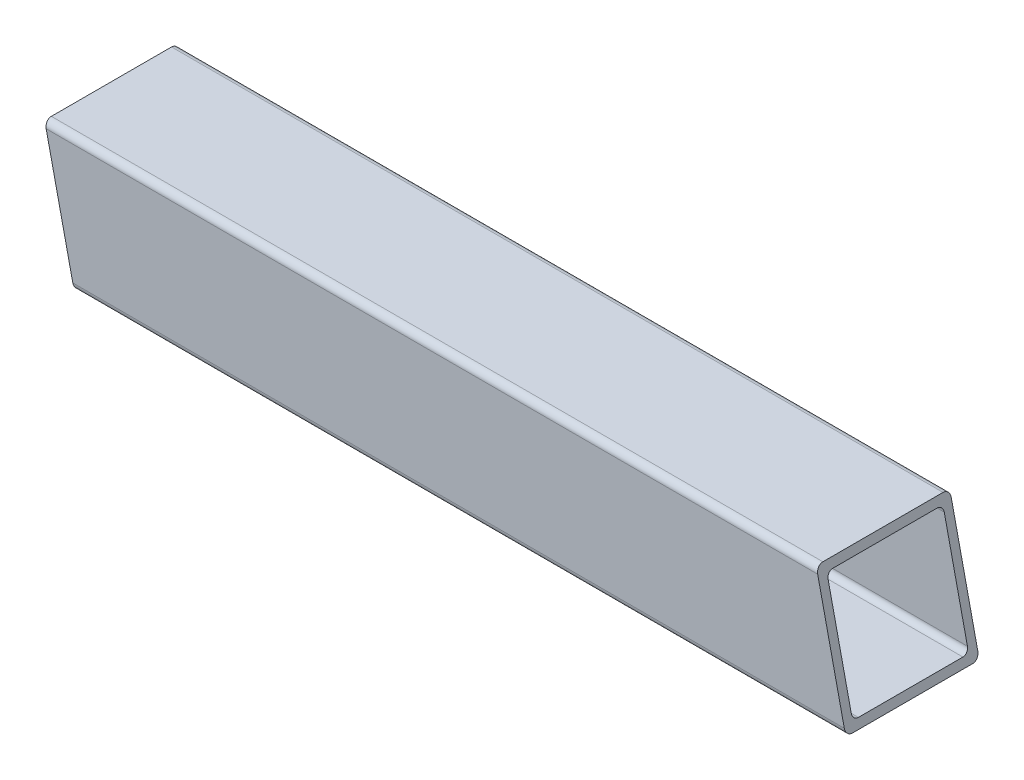
SolidWorks part; units mm, degrees
ref_plane "Front" through (0, 0, 0) normal (0, 0, 1) x (1, 0, 0)
ref_plane "Top" through (0, 0, 0) normal (0, 1, 0) x (1, 0, 0)
ref_plane "Right" through (0, 0, 0) normal (1, 0, 0) x (0, 0, -1)
sketch "Sketch1" plane through (0, 0, 0) normal (1, 0, 0) x (0, 0, -1)
  line L0 (-11.049, 0) -> (-12.7, 0) construction
  line L1 (11.43, -12.7) -> (-11.43, -12.7) construction
  line L2 (12.7, -11.43) -> (12.7, 11.43) construction
  line L3 (11.43, 12.7) -> (-11.43, 12.7) construction
  line L4 (-12.7, -11.43) -> (-12.7, 11.43) construction
  line L5 (12.7, -12.7) -> (-12.7, 12.7) construction
  line L6 (12.7, 12.7) -> (-12.7, -12.7) construction
  line L7 (9.9441, 11.049) -> (-9.9441, 11.049) construction
  line L8 (11.049, 9.9441) -> (11.049, -9.9441) construction
  line L9 (9.9441, -11.049) -> (-9.9441, -11.049) construction
  line L10 (-11.049, 9.9441) -> (-11.049, -9.9441) construction
  line L11 (11.049, 11.049) -> (-11.049, -11.049) construction
  line L12 (11.049, -11.049) -> (-11.049, 11.049) construction
  line L13 (0, -11.049) -> (0, -12.7) construction
  line L14 (11.049, -9.9441) -> (11.049, -12.7) construction
  line L15 (11.049, 0) -> (12.7, 0) construction
  line L16 (11.049, -12.7) -> (12.7, -12.7) construction
  arc A0 (-9.9441, -11.049) -> (-11.049, -9.9441) centre (-9.9441, -9.9441) cw construction
  arc A1 (11.049, -9.9441) -> (9.9441, -11.049) centre (9.9441, -9.9441) cw construction
  arc A2 (9.9441, 11.049) -> (11.049, 9.9441) centre (9.9441, 9.9441) cw construction
  arc A3 (-9.9441, 11.049) -> (-11.049, 9.9441) centre (-9.9441, 9.9441) ccw construction
  arc A4 (11.43, -12.7) -> (12.7, -11.43) centre (11.43, -11.43) ccw construction
  arc A5 (12.7, 11.43) -> (11.43, 12.7) centre (11.43, 11.43) ccw construction
  arc A6 (-11.43, 12.7) -> (-12.7, 11.43) centre (-11.43, 11.43) ccw construction
  arc A7 (-11.43, -12.7) -> (-12.7, -11.43) centre (-11.43, -11.43) cw construction
  point P0 (0, 0)
  point P6 (0, 0)
  dimension "D2" = 1.1049
  dimension "D3" = 1.27
  dimension "Outside Width" = 25.4
  dimension "Ouside Height" = 25.4
  dimension "Inside Height" = 22.098
  dimension "Wall Thickness" = 1.651
sketch "Sketch2" plane through (0, 0, 0) normal (0, 0, 1) x (1, 0, 0)
  line L0 (-76.2, 0) -> (76.2, 0) construction
  point P3 (-52.451, 0)
  point P4 (52.451, 0)
  dimension "Length" = 152.4
  dimension "D1" = 23.749
  dimension "D2" = 23.749
sketch "Sketch4" plane through (0, 0, 0) normal (1, 0, 0) x (0, 0, -1)
  line L8 (12.7, -11.43) -> (12.7, 11.43)
  line L9 (11.43, 12.7) -> (-11.43, 12.7)
  line L10 (-12.7, -11.43) -> (-12.7, 11.43)
  line L11 (11.43, -12.7) -> (-11.43, -12.7)
  line L12 (11.049, 9.9441) -> (11.049, -9.9441)
  line L13 (9.9441, -11.049) -> (-9.9441, -11.049)
  line L14 (-11.049, 9.9441) -> (-11.049, -9.9441)
  line L15 (9.9441, 11.049) -> (-9.9441, 11.049)
  arc A8 (12.7, 11.43) -> (11.43, 12.7) centre (11.43, 11.43) ccw
  arc A9 (-11.43, 12.7) -> (-12.7, 11.43) centre (-11.43, 11.43) ccw
  arc A10 (-12.7, -11.43) -> (-11.43, -12.7) centre (-11.43, -11.43) ccw
  arc A11 (11.43, -12.7) -> (12.7, -11.43) centre (11.43, -11.43) ccw
  arc A12 (9.9441, -11.049) -> (11.049, -9.9441) centre (9.9441, -9.9441) ccw
  arc A13 (-11.049, -9.9441) -> (-9.9441, -11.049) centre (-9.9441, -9.9441) ccw
  arc A14 (-9.9441, 11.049) -> (-11.049, 9.9441) centre (-9.9441, 9.9441) ccw
  arc A15 (11.049, 9.9441) -> (9.9441, 11.049) centre (9.9441, 9.9441) ccw
extrude "Boss-Extrude1" add sketch "Sketch4" along normal up to vertex (76.2 mm away) and the other way up to vertex (76.2 mm away)
sketch "Sketch5" plane through (0, 0, 12.7) normal (0, 0, 1) x (1, 0, 0)
  line L4 (76.2, -12.7) -> (76.2, 12.7)
  line L5 (76.2, 12.7) -> (70.569, 12.7)
  line L6 (76.2, 12.7) -> (-76.2, 12.7) construction
  line L7 (70.569, 12.7) -> (76.2, -12.7)
  line L10 (-76.2, -12.7) -> (-76.2, 12.7)
  line L11 (-76.2, 12.7) -> (-70.569, -12.7)
  line L12 (76.2, -12.7) -> (-76.2, -12.7) construction
  line L13 (-70.569, -12.7) -> (-76.2, -12.7)
  dimension "D1" = 12.5
  dimension "D2" = 12.5
extrude "Cut-Extrude1" cut sketch "Sketch5" against normal through all
equation "\"D3@Sketch1\"=\"Outside Width@Sketch1\"*.05"
equation "\"D2@Sketch1\" = \"Inside Height@Sketch1\" * .05"
equation "\"D1@Sketch2\"=\"Outside Width@Sketch1\"-\"Wall Thickness@Sketch1\""
equation "\"D2@Sketch2\"=\"D1@Sketch2\""
